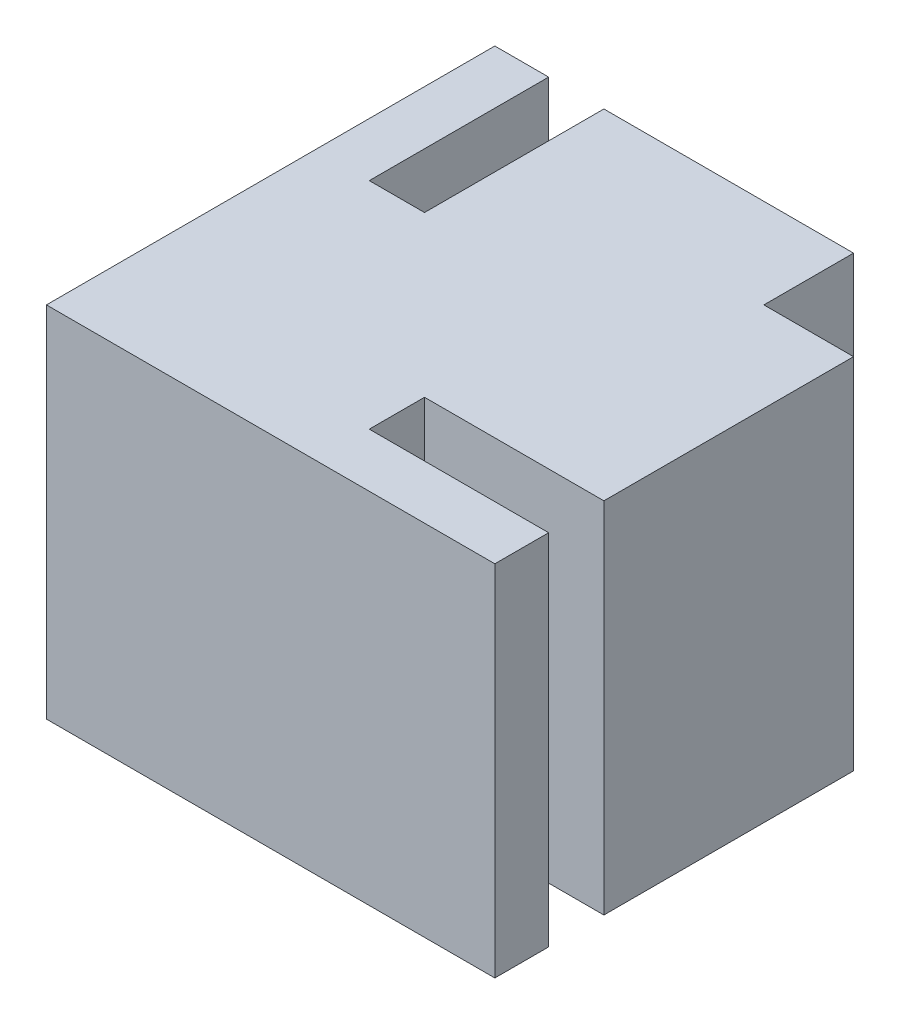
SolidWorks part; units mm, degrees
ref_plane "Alzado" through (0, 0, 0) normal (0, 0, 1) x (1, 0, 0)
ref_plane "Planta" through (0, 0, 0) normal (0, 1, 0) x (1, 0, 0)
ref_plane "Vista lateral" through (0, 0, 0) normal (1, 0, 0) x (0, 0, -1)
sketch "Croquis1" plane through (0, 0, 0) normal (0, 1, 0) x (1, 0, 0)
  line L0 (7.5, 12.5) -> (7.5, 7.5)
  line L1 (-12.5, -12.5) -> (12.5, -12.5)
  line L2 (-12.5, -12.5) -> (-12.5, 12.5)
  line L3 (-12.5, 12.5) -> (7.5, 12.5)
  line L4 (12.5, -12.5) -> (12.5, 7.5)
  line L5 (-12.5, -12.5) -> (7.5, 7.5) construction
  line L6 (-12.5, 12.5) -> (12.5, -12.5) construction
  line L7 (7.5, 7.5) -> (12.5, 7.5)
  point P0 (0, 0)
  point P8 (0, 0)
  dimension "D1" = 25
  dimension "D2" = 25
  dimension "D3" = 20
  dimension "D4" = 20
extrude "Saliente-Extruir1" add sketch "Croquis1" along normal blind 20
sketch "Croquis2" plane through (0, 20, 0) normal (0, 1, 0) x (1, 0, 0)
  line L0 (12.5, 7.5) -> (12.5, -6.42) construction
  line L1 (12.5, -12.5) -> (12.5, 7.5) construction
  line L3 (12.5, -6.42) -> (2.5, -6.42)
  line L4 (12.5, -6.42) -> (12.5, -9.5)
  line L5 (12.5, -9.5) -> (2.5, -9.5)
  line L6 (2.5, -6.42) -> (2.5, -9.5)
  line L7 (7.5, 12.5) -> (-12.5, 12.5) construction
  line L8 (12.5, -12.5) -> (12.5, -9.5) construction
  line L9 (-6.42, 12.5) -> (-9.5, 12.5)
  line L10 (-6.42, 12.5) -> (-6.42, 2.5)
  line L11 (-6.42, 2.5) -> (-9.5, 2.5)
  line L12 (-9.5, 12.5) -> (-9.5, 2.5)
  line L13 (-12.5, 12.5) -> (-9.5, 12.5) construction
  point P8 (0, 0)
  dimension "D1" = 3
  dimension "D2" = 3.08
  dimension "D3" = 10
  dimension "D4" = 3
  dimension "D5" = 3.08
  dimension "D6" = 10
extrude "Cortar-Extruir2" cut sketch "Croquis2" against normal blind 20
